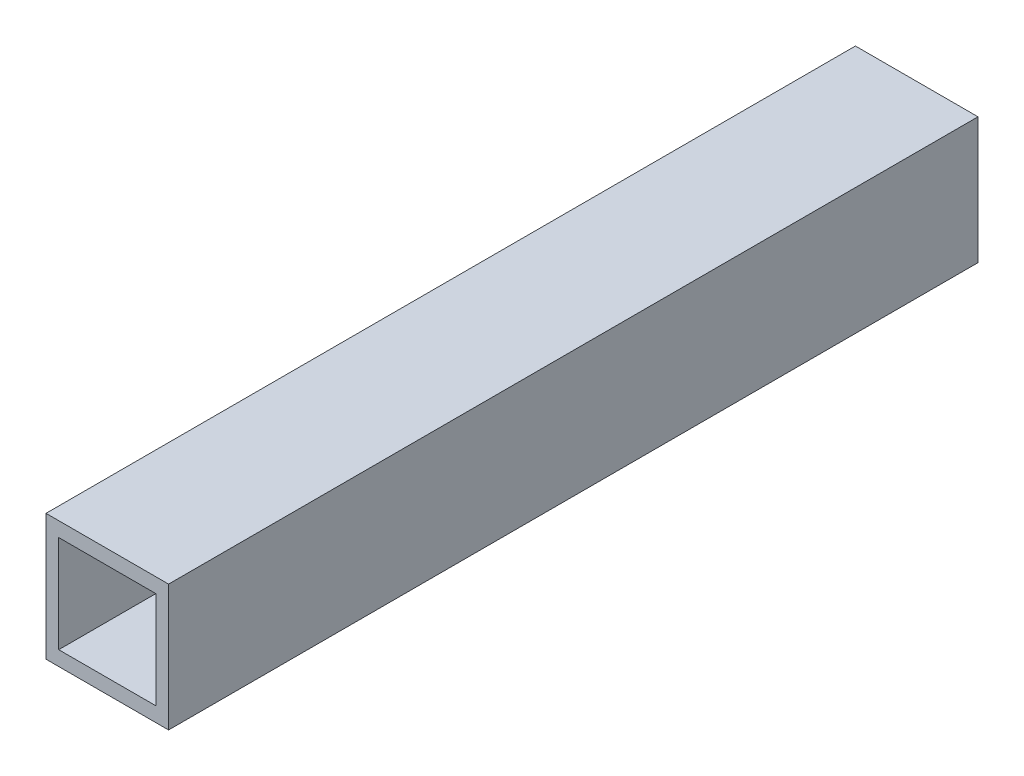
SolidWorks part; units mm, degrees
ref_plane "Front Plane" through (0, 0, 0) normal (0, 0, 1) x (1, 0, 0)
ref_plane "Top Plane" through (0, 0, 0) normal (0, 1, 0) x (1, 0, 0)
ref_plane "Right Plane" through (0, 0, 0) normal (1, 0, 0) x (0, 0, -1)
sketch "Sketch3" plane through (0, 0, 0) normal (0, 0, 1) x (1, 0, 0)
  line L1 (-3.81, -3.81) -> (3.81, -3.81)
  line L2 (-3.81, -3.81) -> (-3.81, 3.81)
  line L3 (-3.81, 3.81) -> (3.81, 3.81)
  line L4 (3.81, -3.81) -> (3.81, 3.81)
  line L5 (-3.81, -3.81) -> (3.81, 3.81) construction
  line L6 (-3.81, 3.81) -> (3.81, -3.81) construction
  line L7 (-4.8085, 4.9561) -> (4.8085, 4.9561)
  line L8 (-4.8085, 4.9561) -> (-4.8085, -4.9561)
  line L9 (-4.8085, -4.9561) -> (4.8085, -4.9561)
  line L10 (4.8085, 4.9561) -> (4.8085, -4.9561)
  line L11 (-4.8085, 4.9561) -> (4.8085, -4.9561) construction
  line L12 (-4.8085, -4.9561) -> (4.8085, 4.9561) construction
  point P0 (0, 0)
extrude "Boss-Extrude2" add sketch "Sketch3" along normal blind 63.5
sketch "Sketch6" plane through (0, -3.81, 0) normal (0, 1, 0) x (1, 0, 0)
  line L0 (0, 0) -> (-3.048, 0)
  line L1 (-3.81, 0) -> (3.81, 0) construction
  line L2 (0, 0) -> (3.048, 0)
  line L3 (3.048, 0) -> (3.048, -1.27)
  line L4 (3.048, -1.27) -> (-3.048, -1.27)
  line L5 (-3.048, -1.27) -> (-3.048, 0)
extrude "Cut-Extrude1" cut sketch "Sketch6" against normal blind 1.27
